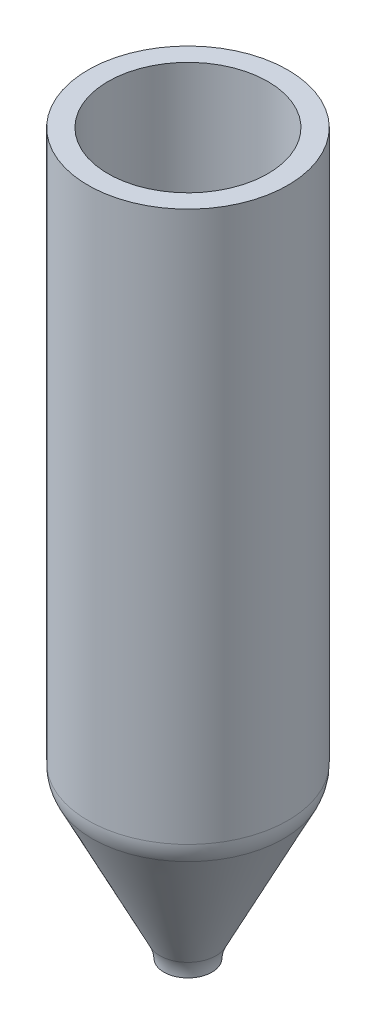
SolidWorks part; units mm, degrees
material "Glass"
ref_plane "Front Plane" through (0, 0, 0) normal (0, 0, 1) x (1, 0, 0)
ref_plane "Top Plane" through (0, 0, 0) normal (0, 1, 0) x (1, 0, 0)
ref_plane "Right Plane" through (0, 0, 0) normal (1, 0, 0) x (0, 0, -1)
sketch "Sketch1" plane through (0, 0, 0) normal (0, 0, 1) x (1, 0, 0)
  line L0 (0.9237, 2.3724) -> (7.2816, 2.3724)
  line L2 (8.615, 7.6046) -> (30.0625, 50.4904)
  line L3 (31.4037, 56.171) -> (31.4037, 230.9724)
  line L4 (31.4037, 230.9724) -> (25.0537, 230.9724)
  line L5 (-0.3463, 2.3732) -> (-0.3463, 379.2333) construction
  line L6 (0.9237, 2.3724) -> (0.9237, 3.4234)
  line L7 (2.265, 9.104) -> (23.7125, 51.9898)
  line L8 (25.0537, 57.6703) -> (25.0537, 230.9724)
  arc A0 (0.9237, 3.4234) -> (2.265, 9.104) centre (13.6237, 3.4234) cw
  arc A1 (23.7125, 51.9898) -> (25.0537, 57.6703) centre (12.3537, 57.6703) ccw
  arc A2 (31.4037, 56.171) -> (30.0625, 50.4904) centre (18.7037, 56.171) cw
  arc A3 (8.615, 7.6046) -> (7.2816, 2.3724) centre (19.9737, 1.924) ccw
  point P16 (31.4037, 53.1724)
  point P19 (7.2738, 4.912)
  dimension "D9" = 12.7
  dimension "D1" = 177.8
  dimension "D2" = 50.8
  dimension "D4" = 1.27
  dimension "D6" = 6.35
  dimension "D7" = 6.35
  dimension "D8" = 25.4
revolve "Revolve1" add sketch "Sketch1" angle 360 about L5
